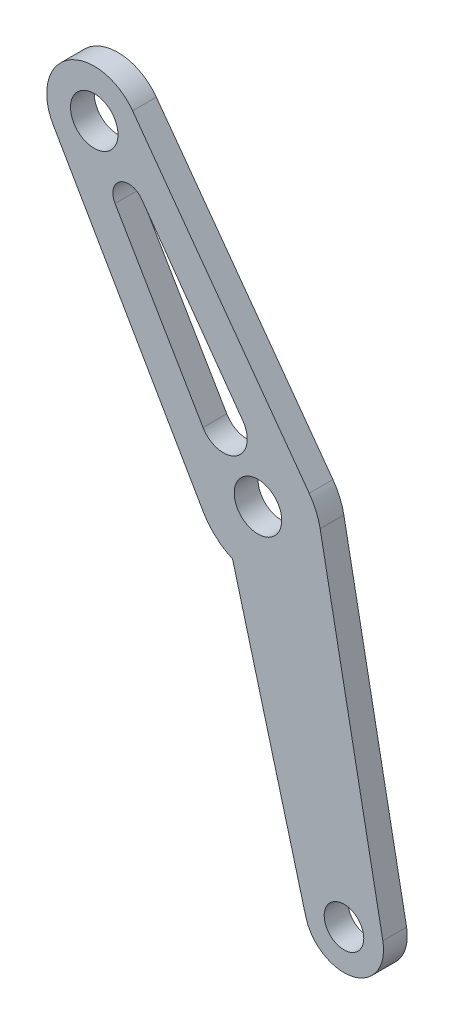
SolidWorks part; units mm, degrees
ref_plane "前视基准面" through (0, 0, 0) normal (0, 0, 1) x (1, 0, 0)
ref_plane "上视基准面" through (0, 0, 0) normal (0, 1, 0) x (1, 0, 0)
ref_plane "右视基准面" through (0, 0, 0) normal (1, 0, 0) x (0, 0, -1)
sketch "草图2" plane through (0, 0, 0) normal (0, 0, 1) x (1, 0, 0)
  line L0 (-1.1837, -107.9266) -> (-1.1837, 28.99) construction
  line L1 (-83.2547, -41.0466) -> (83.2547, -41.0466) construction
  line L3 (-12.0541, -0.4777) -> (-82.4527, 107.9266) construction
  line L4 (-37.9474, 28.3933) -> (-18.9835, -4.4757)
  line L5 (-27.8973, 34.9199) -> (-5.5834, 4.2265)
  line L6 (-15.2674, -7.804) -> (-6.0133, -42.3407)
  line L7 (3.726, -40.1008) -> (-4.1986, 1.0356)
  line L8 (-30.1184, 23.6705) -> (-18.9989, 4.7138)
  line L9 (-26.7672, 25.8468) -> (-13.9721, 7.9782)
  circle A0 centre (-1.1837, -41.0466) radius 2.5
  circle A1 centre (-12.0541, -0.4777) radius 3
  circle A2 centre (-32.7504, 31.3918) radius 3
  arc A3 (-27.8973, 34.9199) -> (-37.9474, 28.3933) centre (-32.7504, 31.3918) ccw
  arc A4 (-6.0133, -42.3407) -> (3.726, -40.1008) centre (-1.1837, -41.0466) ccw
  arc A5 (-18.9835, -4.4757) -> (-15.2674, -7.804) centre (-12.0541, -0.4777) ccw
  arc A6 (-4.1986, 1.0356) -> (-5.5834, 4.2265) centre (-12.0541, -0.4777) ccw
  arc A7 (-26.7672, 25.8468) -> (-30.1184, 23.6705) centre (-28.3933, 24.6824) ccw
  arc A8 (-18.9989, 4.7138) -> (-13.9721, 7.9782) centre (-16.4112, 6.2316) ccw
  dimension "D5" = 5
  dimension "D6" = 6
  dimension "D7" = 6
  dimension "D8" = 12
  dimension "D9" = 16
  dimension "D11" = 5
  dimension "D14" = 4
  dimension "D15" = 6
  dimension "D2" = 42
  dimension "D3" = 33
  dimension "D4" = 38
  dimension "D12" = 8
  dimension "D13" = 8
extrude "凸台-拉伸1" add sketch "草图2" along normal blind 3
